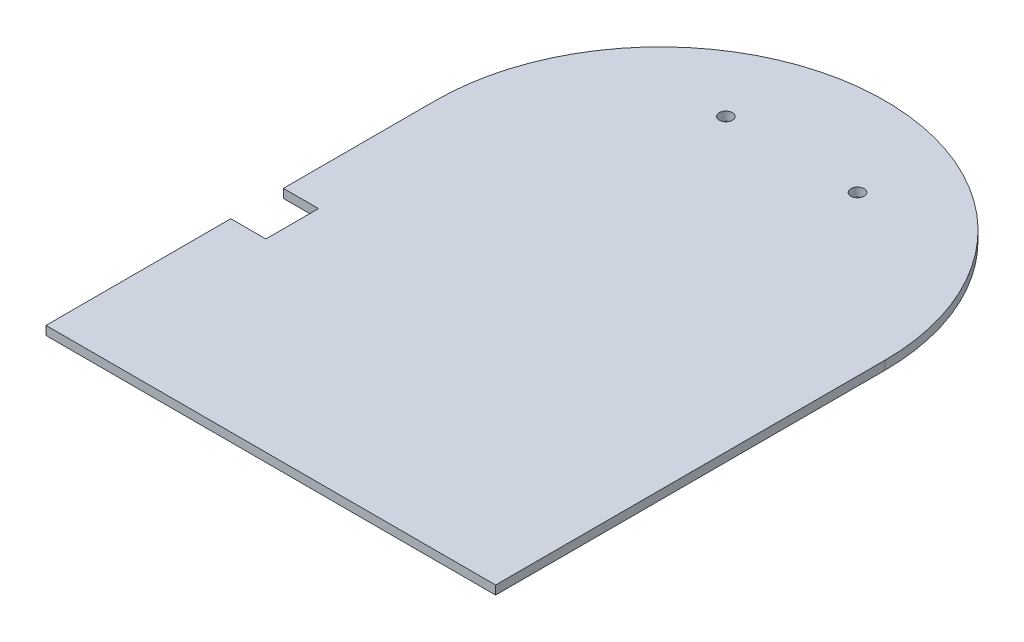
SolidWorks part; units mm, degrees
ref_plane "Plan de face" through (0, 0, 0) normal (0, 0, 1) x (1, 0, 0)
ref_plane "Plan de dessus" through (0, 0, 0) normal (0, 1, 0) x (1, 0, 0)
ref_plane "Plan de droite" through (0, 0, 0) normal (1, 0, 0) x (0, 0, -1)
sketch "Esquisse1" plane through (0, 0, 0) normal (0, 1, 0) x (1, 0, 0)
  line L0 (-51.25, 0) -> (51.25, 0) construction
  line L1 (-51.25, 0) -> (-51.25, -34.6296)
  line L6 (0, 0) -> (0, -131.0207) construction
  line L7 (51.25, 0) -> (51.25, -88.75)
  line L12 (-51.25, -88.75) -> (51.25, -88.75) construction
  line L13 (-51.25, -88.75) -> (51.25, -88.75)
  line L14 (-43.25, -46.6296) -> (-51.25, -46.6296)
  line L15 (-43.25, -46.6296) -> (-43.25, -34.6296)
  line L17 (-43.25, -34.6296) -> (-51.25, -34.6296)
  line L20 (-51.25, -46.6296) -> (-51.25, -88.75)
  arc A0 (-51.25, 0) -> (51.25, 0) centre (0, 0) cw
  point P7 (0, 0)
  point P10 (0, 0)
  dimension "D1" = 140
  dimension "D2" = 102.5
  dimension "D3" = 12
  dimension "D4" = 8
extrude "Boss.-Extru.1" add sketch "Esquisse1" along normal blind 2
sketch "Esquisse4" plane through (0, 2, 0) normal (0, 1, 0) x (1, 0, 0)
  line L4 (0, 19.553) -> (0, 39.1375) construction
  line L6 (-15, 30) -> (15, 30)
  circle A4 centre (15, 30) radius 1.5
  circle A8 centre (-15, 30) radius 1.5
  arc A9 (51.25, 0) -> (-51.25, 0) centre (0, 0) ccw construction
  point P1 (0, 30)
  point P6 (15, 19.0587)
  dimension "D1" = 3
  dimension "D2" = 30
  dimension "D3" = 30
extrude "Enlèv. mat.-Extru.1" cut sketch "Esquisse4" against normal blind 10
